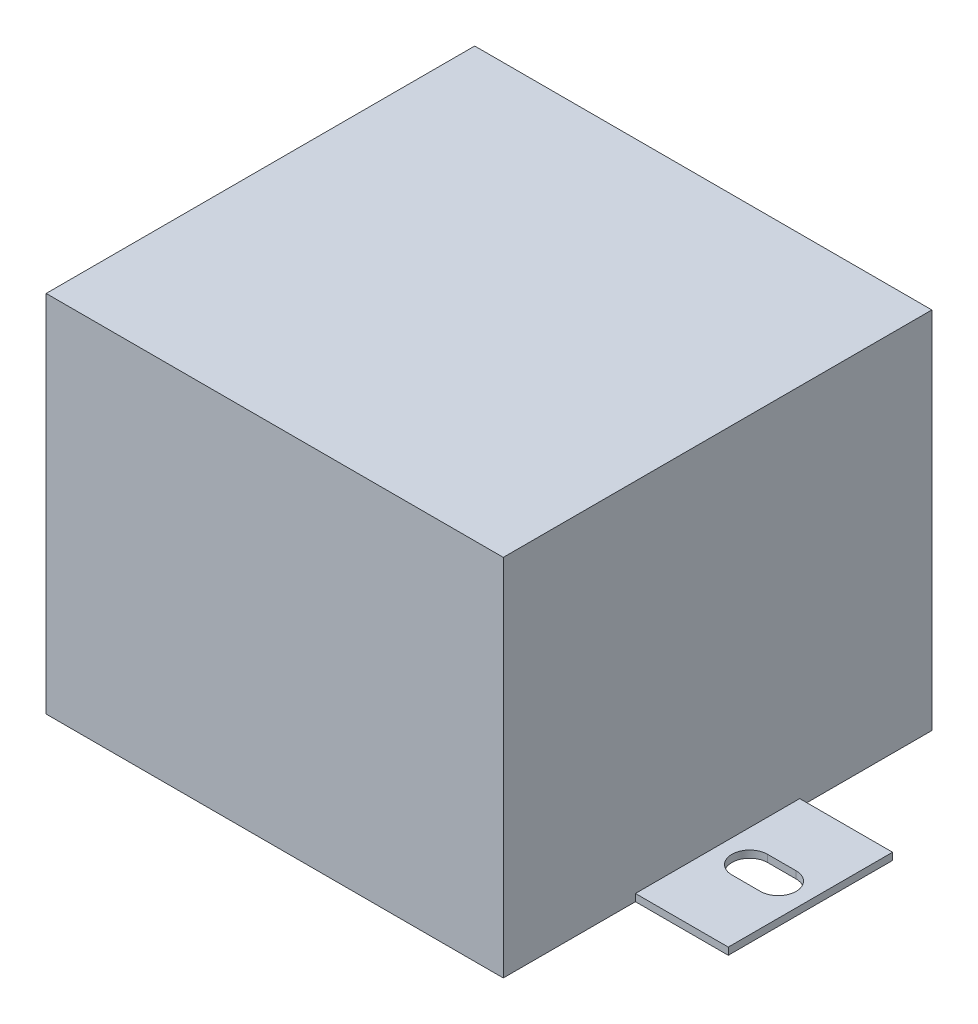
SolidWorks part; units mm, degrees
ref_plane "Alzado" through (0, 0, 0) normal (0, 0, 1) x (1, 0, 0)
ref_plane "Planta" through (0, 0, 0) normal (0, 1, 0) x (1, 0, 0)
ref_plane "Vista lateral" through (0, 0, 0) normal (1, 0, 0) x (0, 0, -1)
sketch "Croquis1" plane through (0, 0, 0) normal (0, 1, 0) x (1, 0, 0)
  line L0 (-32, 11.5) -> (-45, 11.5)
  line L1 (-45, 11.5) -> (-45, -11.5)
  line L2 (-45, -11.5) -> (-32, -11.5)
  line L3 (-32, -11.5) -> (-32, -30)
  line L4 (-32, -30) -> (32, -30)
  line L5 (32, -30) -> (32, -11.5)
  line L6 (32, -11.5) -> (45, -11.5)
  line L7 (45, -11.5) -> (45, 11.5)
  line L8 (45, 11.5) -> (32, 11.5)
  line L9 (32, 11.5) -> (32, 30)
  line L10 (32, 30) -> (-32, 30)
  line L11 (-32, 30) -> (-32, 11.5)
  line L12 (-45, 0) -> (45, 0) construction
  line L13 (-40.5, -2.5) -> (-36.5, -2.5)
  line L14 (-40.5, 2.5) -> (-36.5, 2.5)
  line L15 (0, 30) -> (0, -30) construction
  line L16 (40.5, -2.5) -> (36.5, -2.5)
  line L17 (40.5, 2.5) -> (36.5, 2.5)
  arc A0 (-40.5, -2.5) -> (-40.5, 2.5) centre (-40.5, 0) cw
  arc A1 (-36.5, -2.5) -> (-36.5, 2.5) centre (-36.5, 0) ccw
  arc A2 (40.5, -2.5) -> (40.5, 2.5) centre (40.5, 0) ccw
  arc A3 (36.5, -2.5) -> (36.5, 2.5) centre (36.5, 0) cw
  point P14 (0, 0)
  point P30 (0, 0)
  point P31 (0, 0)
  dimension "D12" = 2.5
  dimension "D15" = 2.5
  dimension "D16" = 11.5
  dimension "D2" = 13
  dimension "D3" = 13
  dimension "D4" = 13
  dimension "D5" = 13
  dimension "D6" = 23
  dimension "D7" = 23
  dimension "D8" = 60
  dimension "D9" = 18.5
  dimension "D10" = 18.5
  dimension "D11" = 90
  dimension "D13" = 4
  dimension "D14" = 4.5
extrude "Saliente-Extruir1" add sketch "Croquis1" along normal blind 1
sketch "Croquis2" plane through (0, 1, 0) normal (0, 1, 0) x (1, 0, 0)
  line L1 (-32, 30) -> (32, 30)
  line L2 (-32, 30) -> (-32, -30)
  line L3 (-32, -30) -> (32, -30)
  line L4 (32, 30) -> (32, -30)
extrude "Saliente-Extruir2" add sketch "Croquis2" along normal blind 50
